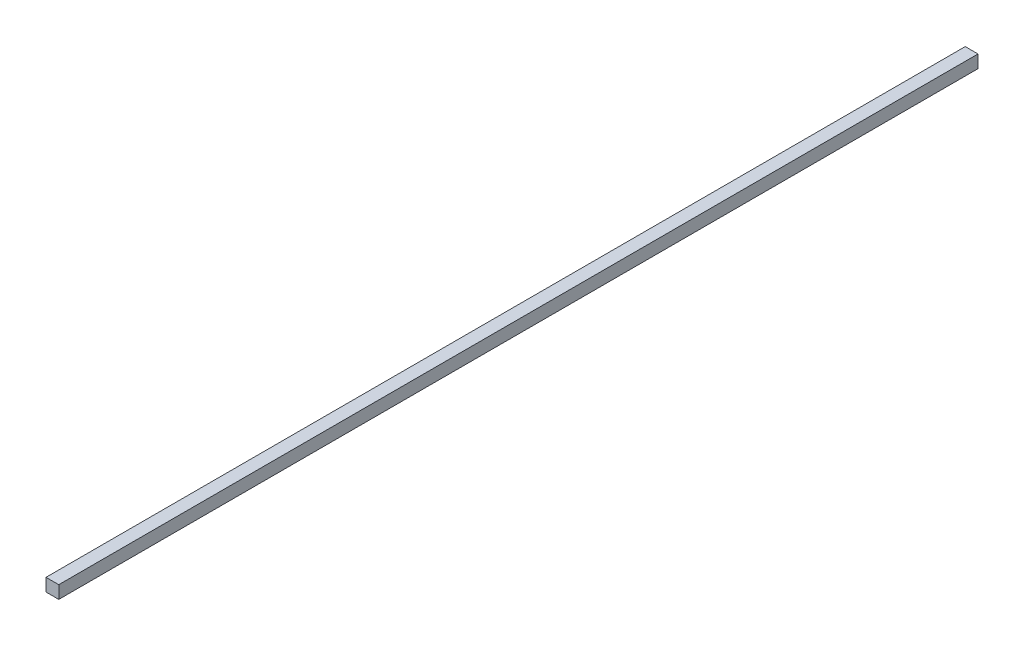
SolidWorks part; units mm, degrees
ref_plane "Front Plane" through (0, 0, 0) normal (0, 0, 1) x (1, 0, 0)
ref_plane "Top Plane" through (0, 0, 0) normal (0, 1, 0) x (1, 0, 0)
ref_plane "Right Plane" through (0, 0, 0) normal (1, 0, 0) x (0, 0, -1)
sketch "Sketch1" plane through (0, 0, 0) normal (0, 0, 1) x (1, 0, 0)
  line L1 (-10, -10) -> (10, -10)
  line L2 (-10, -10) -> (-10, 10)
  line L3 (-10, 10) -> (10, 10)
  line L4 (10, -10) -> (10, 10)
  line L5 (-10, -10) -> (10, 10) construction
  line L6 (-10, 10) -> (10, -10) construction
  point P0 (0, 0)
  dimension "D1" = 20
extrude "Boss-Extrude1" add sketch "Sketch1" along normal blind 1440
